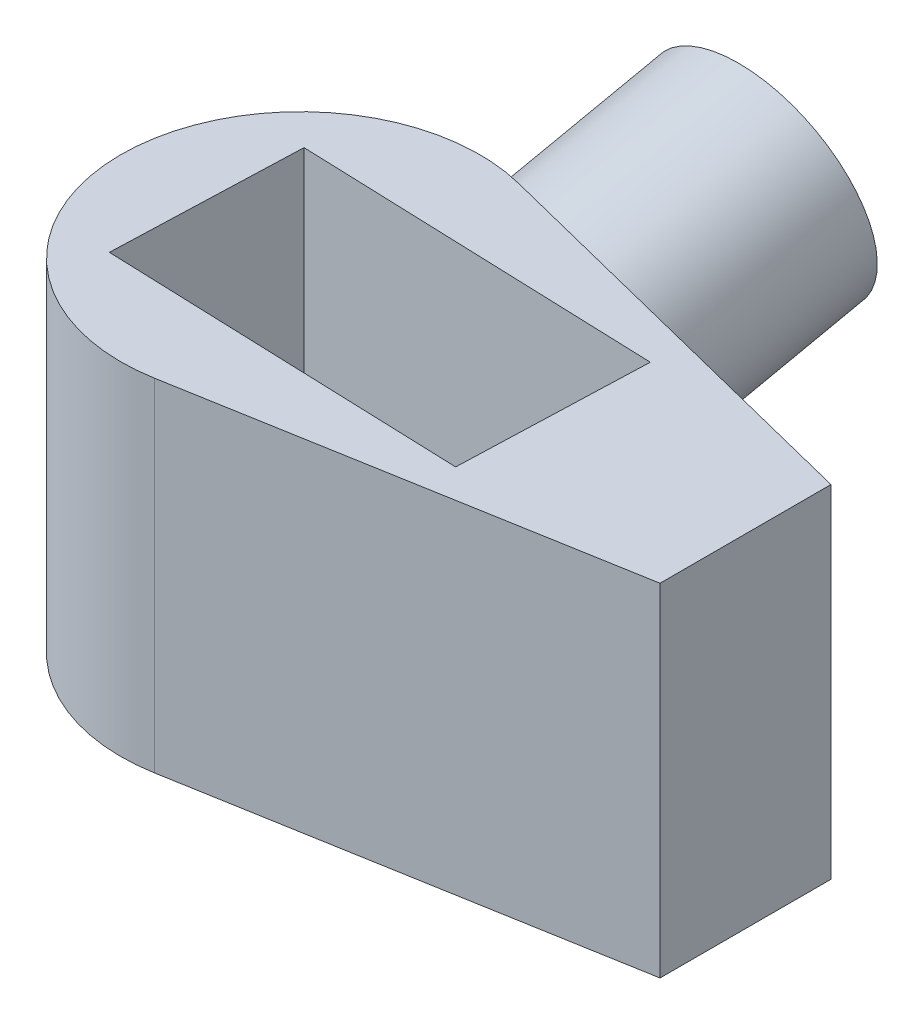
SolidWorks part; units mm, degrees
material "3.0205 (EN-AW 1200)"
ref_plane "Alzado" through (0, 0, 0) normal (0, 0, 1) x (1, 0, 0)
ref_plane "Planta" through (0, 0, 0) normal (0, 1, 0) x (1, 0, 0)
ref_plane "Vista lateral" through (0, 0, 0) normal (1, 0, 0) x (0, 0, -1)
sketch "Croquis1" plane through (0, 0, 0) normal (0, 1, 0) x (1, 0, 0)
  circle A0 centre (0, 0) radius 21
  dimension "D1" = 42
extrude "Saliente-Extruir1" add sketch "Croquis1" along normal blind 40
sketch "Croquis2" plane through (0, 0, 0) normal (0, 1, 0) x (1, 0, 0)
  line L0 (53.9751, 8.111) -> (53.9751, -11.889)
  line L1 (53.9751, -11.889) -> (3.6138, -20.6867)
  line L2 (53.9751, 8.111) -> (5.1095, 20.3689)
  circle A0 centre (0, 0) radius 21 construction
  arc A1 (3.6138, -20.6867) -> (5.1095, 20.3689) centre (0, 0) ccw
  dimension "D1" = 20
extrude "Saliente-Extruir2" add sketch "Croquis2" along normal blind 40
sketch "Croquis3" plane through (5.1095, 0, -20.3689) normal (0.2433, 0, -0.9699) x (-0.9699, 0, -0.2433)
  line L0 (0, 40) -> (0, 0) construction
  circle A0 centre (0, 20) radius 10
  circle A1 centre (0, 20) radius 13.5
  dimension "D1" = 20
  dimension "D2" = 27
extrude "Saliente-Extruir3" add sketch "Croquis3" against normal up to surface (2.5338 mm away)
ref_plane "Plano1" through (5.1, 0, 0) normal (1, 0, 0) x (0, 0, -1)
sketch "Croquis4" plane through (5.1, 0, 0) normal (1, 0, 0) x (0, 0, -1)
  line L0 (16.629, 5.9455) -> (51.6687, 13.4008)
  line L1 (23.4687, 7.4008) -> (51.6687, 7.4008)
  line L2 (51.6687, 7.4008) -> (51.6687, 13.4008)
  line L3 (23.4687, 10.9008) -> (51.6687, 16.9008)
  line L4 (51.6687, 16.9008) -> (51.6687, 13.4008)
  line L5 (16.629, 9.4455) -> (16.629, 5.9455)
  line L6 (23.4687, 10.9008) -> (16.629, 9.4455)
  line L7 (23.4687, 20.9008) -> (47.142, 25.9377)
  line L10 (-1.889, 40) -> (-1.889, 0)
  line L11 (-11.889, 40) -> (8.111, 40) construction
  line L12 (-11.889, 0) -> (8.111, 0) construction
sketch "Croquis7" plane through (0, 0, 0) normal (0, -1, 0) x (1, 0, 0)
  circle A0 centre (0, 0) radius 6
  circle A1 centre (0, 0) radius 8.2273
  dimension "D1" = 16.4545
  dimension "D2" = 12
extrude "Cortar-Extruir6" cut sketch "Croquis7" against normal blind 6
sketch "Croquis8" plane through (0, 0, 0) normal (0, -1, 0) x (1, 0, 0)
  circle A0 centre (0, 0) radius 6
extrude "Cortar-Extruir7" cut sketch "Croquis8" against normal through all
sketch "Croquis10" plane through (0, 40, 0) normal (0, 1, 0) x (1, 0, 0)
  line L0 (-11.3782, 0.4245) -> (30.6218, -1.0623)
  line L1 (-10.9888, 11.4245) -> (31.0112, 9.9377)
  line L2 (-10.9888, 11.4245) -> (-11.7676, -10.5755)
  line L3 (31.0112, 9.9377) -> (30.2324, -12.0623)
  line L4 (-11.7676, -10.5755) -> (30.2324, -12.0623)
  line L5 (37.4945, -5.951) -> (37.4945, -5.9648)
  line L7 (53.9751, -1.889) -> (-20.9861, 0.7646)
  line L8 (53.9751, -11.889) -> (53.9751, 8.111) construction
  arc A0 (5.1095, 20.3689) -> (3.6138, -20.6867) centre (0, 0) ccw construction
  point P7 (16.4945, -0.5622)
  circle M7 centre (0, 0) radius 6
  dimension "D1" = 11
  dimension "D2" = 42
extrude "Cortar-Extruir8" cut sketch "Croquis10" against normal blind 25 contours L2 L4 L3 L0 M7 | L3 L1 L2 L0 M7
sketch "Croquis12" plane through (0, 15, 0) normal (0, 1, 0) x (1, 0, 0)
  circle A0 centre (0, 0) radius 9.55
  dimension "D1" = 19.1
extrude "Cortar-Extruir9" cut sketch "Croquis12" against normal blind 5.5
revolve "Revolución2" add sketch "Croquis4" angle 360 about L7
